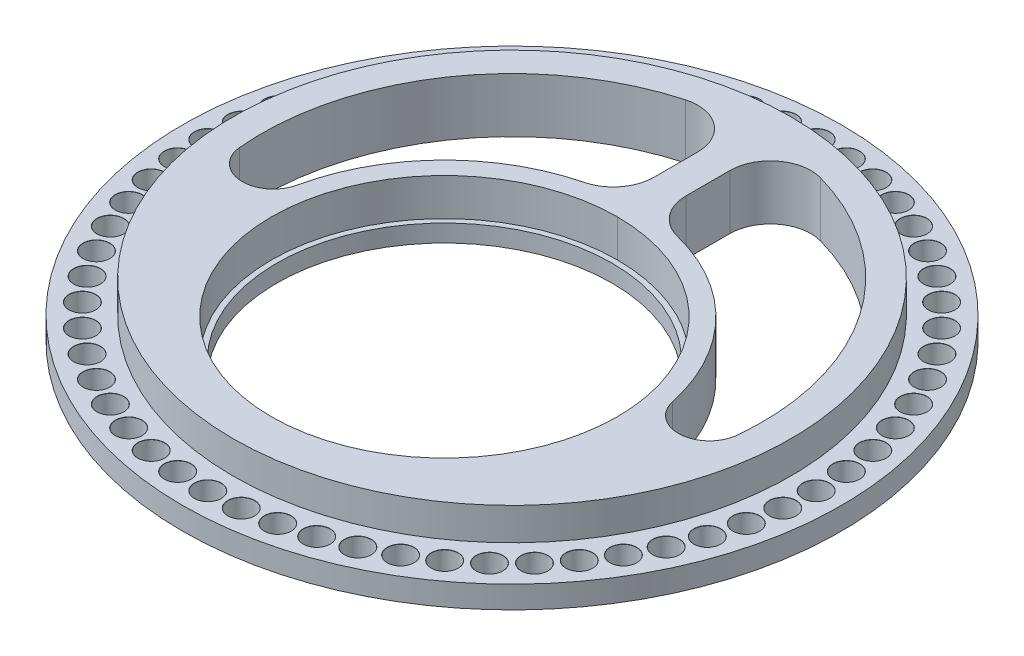
SolidWorks part; units mm, degrees
material "6061-T6 (SS)"
ref_plane "X-Y Datum" through (0, 0, 0) normal (0, 0, 1) x (1, 0, 0)
ref_plane "X-Z Datum" through (0, 0, 0) normal (0, 1, 0) x (1, 0, 0)
ref_plane "Y-Z Datum" through (0, 0, 0) normal (1, 0, 0) x (0, 0, -1)
sketch "Sketch1" plane through (0, 0, 0) normal (0, 1, 0) x (1, 0, 0)
  line L0 (0, 0) -> (0, -12.7) construction
  line L1 (0, -43.0151) -> (0, 43.0151) construction
  line L2 (0, 52.3875) -> (0, 61.9125) construction
  circle A0 centre (0, -12.7) radius 30.988
  circle A1 centre (0, 0) radius 52.3875 construction
  circle A2 centre (0, 0) radius 61.9125
  circle A3 centre (0, 0) radius 57.15 construction
  point P12 (0, 57.15)
  dimension "D2" = 61.976
  dimension "D3" = 104.775
  dimension "D4" = 123.825
  dimension "D5" = 114.3
  dimension "D1" = 12.7
extrude "Slotted-Body Extrude" add sketch "Sketch1" along normal blind 4.191
sketch "Sketch5" plane through (0, 4.191, 0) normal (0, 1, 0) x (1, 0, 0)
  circle A0 centre (0, 0) radius 52.3875 construction
  circle A1 centre (0, 0) radius 52.3875
extrude "Boss-Extrude3" add sketch "Sketch5" along normal blind 6.08
sketch "Sketch6" plane through (0, 0, 0) normal (0, -1, 0) x (1, 0, 0)
  line L0 (0, -79.2756) -> (0, 0) construction
  line L2 (3.014, -37.9067) -> (3.014, -29.6741)
  line L4 (-3.014, -37.9067) -> (-3.014, -29.6741)
  circle A0 centre (0, 12.7) radius 30.988 construction
  circle A1 centre (0, 12.7) radius 30.988 construction
  circle A2 centre (0, 12.7) radius 32.512
  arc A9 (-35.2562, 5.0907) -> (-8.7792, -22.2832) centre (0, 12.7) ccw
  arc A10 (-46.783, 4.406) -> (-12.6921, -45.2435) centre (0, 0) ccw
  arc A11 (-46.783, 4.406) -> (-35.2562, 5.0907) centre (-40.9667, 3.8583) cw
  arc A19 (-3.014, -29.6741) -> (-8.7792, -22.2832) centre (-10.634, -29.6741) ccw
  arc A20 (-3.014, -37.9067) -> (-12.6921, -45.2435) centre (-10.634, -37.9067) cw
  circle A21 centre (0, 0) radius 61.9125 construction
  arc A27 (46.783, 4.406) -> (35.2562, 5.0907) centre (40.9667, 3.8583) ccw
  arc A28 (46.783, 4.406) -> (12.6921, -45.2435) centre (0, 0) cw
  arc A29 (3.014, -37.9067) -> (12.6921, -45.2435) centre (10.634, -37.9067) ccw
  arc A30 (3.014, -29.6741) -> (8.7792, -22.2832) centre (10.634, -29.6741) cw
  arc A31 (35.2562, 5.0907) -> (8.7792, -22.2832) centre (0, 12.7) cw
  point P30 (0, 0)
  point P31 (-3.014, -23.2419)
  point P32 (0, 0)
  point P36 (-3.014, -46.8932)
  dimension "D1" = 65.024
  dimension "D2" = 7.62
  dimension "D3" = 5.842
  dimension "D4" = 46.99
  dimension "D5" = 7.62
  dimension "D6" = 36.068
  dimension "D8" = 8.2326
extrude "Cut-Extrude5" cut sketch "Sketch6" against normal through all
sketch "Sketch8" plane through (0, 0, 0) normal (0, -1, 0) x (1, 0, 0)
  circle A0 centre (0, 12.7) radius 32.512 construction
  circle A1 centre (0, 12.7) radius 32.512
  circle A2 centre (0, 12.7) radius 31.496
  dimension "D1" = 62.992
extrude "Boss-Extrude4" add sketch "Sketch8" against normal blind 3.255 separate body
hole_wizard "Ø5.0mm Dowel Hole1" positions "Sketch9" profile "Sketch10" hole size "Ø5.0" standard "ANSI Metric" end condition through all
sketch "Sketch9" plane through (0, 4.191, 0) normal (0, 1, 0) x (1, 0, 0)
  point P0 (0, 57.15)
sketch "Sketch10" plane through (0, 4.191, -57.15) normal (1, 0, 0) x (0, 0, 1)
  line L0 (0, 0) -> (0, 4.191)
  line L1 (0, 4.191) -> (2.5, 4.191)
  line L2 (2.5, 4.191) -> (2.5, 0.025)
  line L3 (2.5, 0.025) -> (2.525, 0)
  line L5 (2.525, 0) -> (0, 0)
  line L6 (-2.5, 0.025) -> (-2.525, 0) construction
  line L11 (0, -6.35) -> (0, 107.95) construction
  dimension "Thru Hole Dia." = 5
  dimension "Thru Hole Depth" = 4.191
  dimension "Near C'Sink Dia." = 5.05
  dimension "Near C'Sink Angle" = 90
pattern_circular "CirPattern1" count 60 over 360 about axis through (0, 0, 0) along (0, 1, 0) of "Ø5.0mm Dowel Hole1"
ref_point "Point1"
ref_plane "Plane1" through (0, 0, 0) normal (1, 0, 0) x (0, 0, -1)
split line "Split Line1"
curve "CompCurve1"
